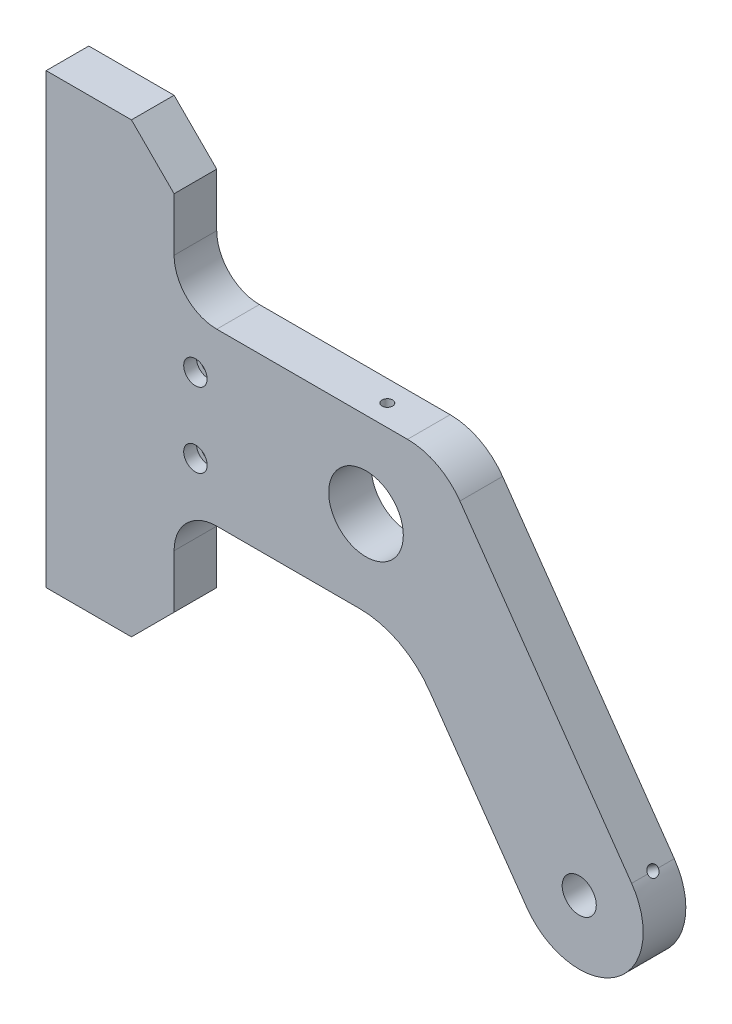
SolidWorks part; units mm, degrees
material "普通碳钢"
ref_plane "前视基准面" through (0, 0, 0) normal (0, 0, 1) x (1, 0, 0)
ref_plane "上视基准面" through (0, 0, 0) normal (0, 1, 0) x (1, 0, 0)
ref_plane "右视基准面" through (0, 0, 0) normal (1, 0, 0) x (0, 0, -1)
sketch "草图1" plane through (0, 0, 0) normal (0, 0, 1) x (1, 0, 0)
  line L0 (0, 105) -> (358.1423, 105) construction
  line L1 (185.0931, 145) -> (167.8633, 65) construction
  line L2 (0, 210) -> (60, 210)
  line L3 (60, 145) -> (60, 210)
  line L4 (0, 210) -> (0, 0)
  line L5 (60, 65) -> (167.8633, 65)
  line L6 (167.8633, 65) -> (225.4254, -17.2073)
  line L7 (185.0931, 145) -> (60, 145)
  line L8 (60, 0) -> (0, 0)
  line L9 (60, 65) -> (60, 0)
  line L10 (274.5746, 17.2073) -> (185.0931, 145)
  arc A0 (225.4254, -17.2073) -> (274.5746, 17.2073) centre (250, 0) ccw
  dimension "D4" = 105
  dimension "D5" = 55
  dimension "D1" = 210
  dimension "D2" = 60
  dimension "D3" = 80
  dimension "D6" = 60
  dimension "D7" = 250
extrude "凸台-拉伸1" add sketch "草图1" along normal mid plane 20
chamfer "倒角1" distance 20 angle 45 2 edges at (60, 0, 0) (60, 210, 0)
fillet "圆角1" radius 20 2 edges at (60, 65, 0) (60, 145, 0)
fillet "圆角2" radius 30 1 edges at (185.0931, 145, 0)
fillet "圆角3" radius 40 1 edges at (167.8633, 65, 0)
hole_wizard "M10 螺纹孔1" positions "草图3" profile "草图2" tap size "M10" standard "GB"
sketch "草图3" plane through (0, 0, 0) normal (-1, 0, 0) x (0, 0, 1)
  line L0 (0, 210) -> (0, 0) construction
  line L1 (10, 210) -> (-10, 210) construction
  line L3 (10, 105) -> (-10, 105) construction
  line L4 (10, 210) -> (10, 0) construction
  line L5 (-10, 210) -> (-10, 0) construction
  point P0 (0, 195)
  point P1 (0, 135)
  point P7 (0, 75)
  point P9 (0, 15)
  dimension "D2" = 60
  dimension "D3" = 180
sketch "草图2" plane through (0, 195, 0) normal (0, 1, 0) x (0, 0, 1)
  line L0 (0, 0) -> (0, 27.5537)
  line L1 (0, 27.5537) -> (4.25, 25)
  line L2 (4.25, 25) -> (4.25, 0)
  line L5 (4.25, 0) -> (0, 0)
  line L10 (0, 27.5537) -> (-4.25, 25) construction
  line L11 (0, -6.35) -> (0, 107.95) construction
  dimension "螺纹孔钻头直径" = 8.5
  dimension "螺纹孔钻头深度" = 25
  dimension "导头角度" = 118
cosmetic thread "孔螺蚊线1" parameters "D1"=20, "D2"=10
cosmetic thread "孔螺蚊线2" parameters "D1"=20, "D2"=10
cosmetic thread "孔螺蚊线3" parameters "D1"=20, "D2"=10
cosmetic thread "孔螺蚊线4" parameters "D1"=20, "D2"=10
hole_wizard "M6 凹头盖螺钉的柱形沉头孔1" positions "草图5" profile "草图6" counterbore size "M6" standard "Ansi Metric" end condition through all
sketch "草图5" plane through (0, 0, 10) normal (0, 0, 1) x (1, 0, 0)
  line L0 (0, 105) -> (109.9409, 105) construction
  line L1 (0, 210) -> (0, 0) construction
  point P0 (70, 122.5)
  point P1 (70, 87.5)
  dimension "D1" = 70
  dimension "D2" = 35
sketch "草图6" plane through (70, 122.5, 10) normal (1, 0, 0) x (0, -1, 0)
  line L0 (0, 0) -> (0, 20)
  line L1 (0, 20) -> (3.25, 20)
  line L3 (3.25, 20) -> (3.25, 6)
  line L4 (3.25, 6) -> (5.5, 6)
  line L5 (5.5, 6) -> (5.5, 0)
  line L7 (5.5, 0) -> (0, 0)
  line L11 (0, -6.35) -> (0, 107.95) construction
  dimension "通孔孔直径" = 6.5
  dimension "通孔孔深度" = 20
  dimension "柱形沉头孔直径" = 11
  dimension "柱形沉头孔深度" = 6
hole_wizard "孔1" positions "草图8" profile "草图9" legacy end condition through all
sketch "草图8" plane through (0, 0, 10) normal (0, 0, 1) x (1, 0, 0)
  line L0 (0, 105) -> (286.8897, 105) construction
  line L1 (0, 210) -> (0, 0) construction
  point P0 (150, 105)
  dimension "D1" = 150
sketch "草图9" plane through (150, 105, 10) normal (1, 0, 0) x (0, -1, 0)
  line L0 (0, 0) -> (0, 20)
  line L1 (0, 20) -> (17.5, 20)
  line L2 (17.5, 20) -> (17.5, 0)
  line L3 (17.5, 0) -> (0, 0)
  line L4 (0, 110) -> (0, -10) construction
  dimension "直径" = 35
  dimension "深度" = 20
hole_wizard "孔2" positions "草图11" profile "草图10" legacy
sketch "草图11" plane through (0, 0, 10) normal (0, 0, 1) x (1, 0, 0)
  point P0 (250, 0)
sketch "草图10" plane through (250, 0, 10) normal (1, 0, 0) x (0, -1, 0)
  line L0 (0, 0) -> (0, 38)
  line L1 (0, 38) -> (8, 38)
  line L2 (8, 38) -> (8, 0)
  line L3 (8, 0) -> (0, 0)
  line L4 (0, 110) -> (0, -10) construction
  dimension "直径" = 16
  dimension "深度" = 38
hole_wizard "M6 螺纹孔1" positions "草图13" profile "草图14" tap size "M6" standard "GB"
sketch "草图13" plane through (0, 145, 0) normal (0, 1, 0) x (-1, 0, 0)
  line L0 (-169.4761, 0) -> (-130.5239, 0) construction
  line L1 (-169.4761, 10) -> (-169.4761, -10) construction
  point P0 (-150, 0)
  dimension "D1" = 150
sketch "草图14" plane through (150, 145, 0) normal (1, 0, 0) x (0, 0, 1)
  line L0 (0, 0) -> (0, 16.5022)
  line L1 (0, 16.5022) -> (2.5, 15)
  line L2 (2.5, 15) -> (2.5, 0)
  line L5 (2.5, 0) -> (0, 0)
  line L10 (0, 16.5022) -> (-2.5, 15) construction
  line L11 (0, -6.35) -> (0, 107.95) construction
  dimension "螺纹孔钻头直径" = 5
  dimension "螺纹孔钻头深度" = 15
  dimension "导头角度" = 118
cosmetic thread "孔螺蚊线6" parameters "D1"=12, "D2"=6
hole_wizard "M6 螺纹孔2" positions "草图16" profile "草图17" tap size "M6" standard "GB"
sketch "草图16" plane through (192.3271, 134.6689, 0) normal (0.8192, 0.5736, 0) x (0, 0, -1)
  line L0 (-10, -143.3941) -> (10, -143.3941) construction
  point P1 (0, -143.3941)
sketch "草图17" plane through (274.5746, 17.2073, 0) normal (0, 0, 1) x (-0.5736, 0.8192, 0)
  line L0 (0, 0) -> (0, 16.5022)
  line L1 (0, 16.5022) -> (2.5, 15)
  line L2 (2.5, 15) -> (2.5, 0)
  line L5 (2.5, 0) -> (0, 0)
  line L10 (0, 16.5022) -> (-2.5, 15) construction
  line L11 (0, -6.35) -> (0, 107.95) construction
  dimension "螺纹孔钻头直径" = 5
  dimension "螺纹孔钻头深度" = 15
  dimension "导头角度" = 118
cosmetic thread "孔螺蚊线5" parameters "D1"=12, "D2"=6
